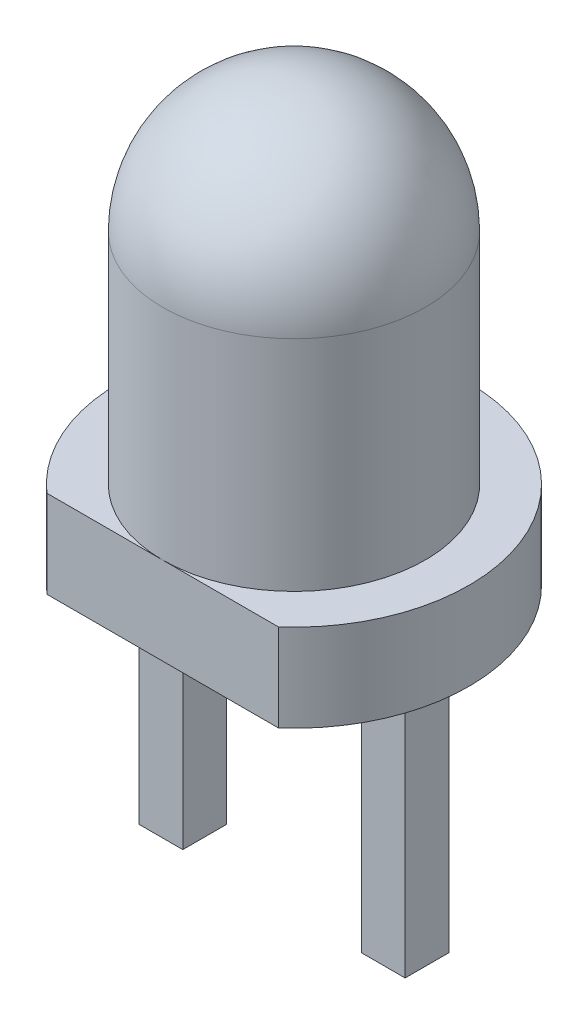
SolidWorks part; units mm, degrees
ref_plane "Front Plane" through (0, 0, 0) normal (0, 0, 1) x (1, 0, 0)
ref_plane "Top Plane" through (0, 0, 0) normal (0, 1, 0) x (1, 0, 0)
ref_plane "Right Plane" through (0, 0, 0) normal (1, 0, 0) x (0, 0, -1)
sketch "Sketch1" plane through (0, 0, 0) normal (1, 0, 0) x (0, 0, -1)
  line L0 (-1.5, 0) -> (-1.5, 3.5)
  line L1 (0, 5) -> (0, 0) construction
  line L2 (0, 0) -> (-1.5, 0)
  line L3 (0, 5) -> (0, 0)
  arc A0 (-1.5, 3.5) -> (0, 5) centre (0, 3.5) cw
  dimension "D1" = 3
  dimension "D2" = 5
revolve "Revolve1" add sketch "Sketch1" angle 360 about L1
sketch "Sketch2" plane through (0, 0, 0) normal (0, 1, 0) x (1, 0, 0)
  line L0 (-1.3229, -1.5) -> (1.3229, -1.5)
  arc A0 (1.3229, -1.5) -> (-1.3229, -1.5) centre (0, 0) ccw
  circle A1 centre (0, 0) radius 1.5 construction
  dimension "D1" = 4
extrude "Boss-Extrude1" add sketch "Sketch2" along normal blind 1
sketch "Sketch3" plane through (0, 0, 0) normal (0, -1, 0) x (1, 0, 0)
  line L1 (-1.52, 0.25) -> (-1.02, 0.25)
  line L2 (-1.52, 0.25) -> (-1.52, -0.25)
  line L3 (-1.52, -0.25) -> (-1.02, -0.25)
  line L4 (-1.02, 0.25) -> (-1.02, -0.25)
  line L5 (1.02, 0.25) -> (1.52, 0.25)
  line L6 (1.02, 0.25) -> (1.02, -0.25)
  line L7 (1.02, -0.25) -> (1.52, -0.25)
  line L8 (1.52, 0.25) -> (1.52, -0.25)
  point P8 (-1.02, 0)
  point P9 (1.02, 0)
  point P11 (-1.27, 0.25)
  point P12 (1.27, 0.25)
  dimension "D1" = 0.5
  dimension "D2" = 2.54
  dimension "D3" = 1.27
extrude "Boss-Extrude2" add sketch "Sketch3" along normal blind 3 separate body
